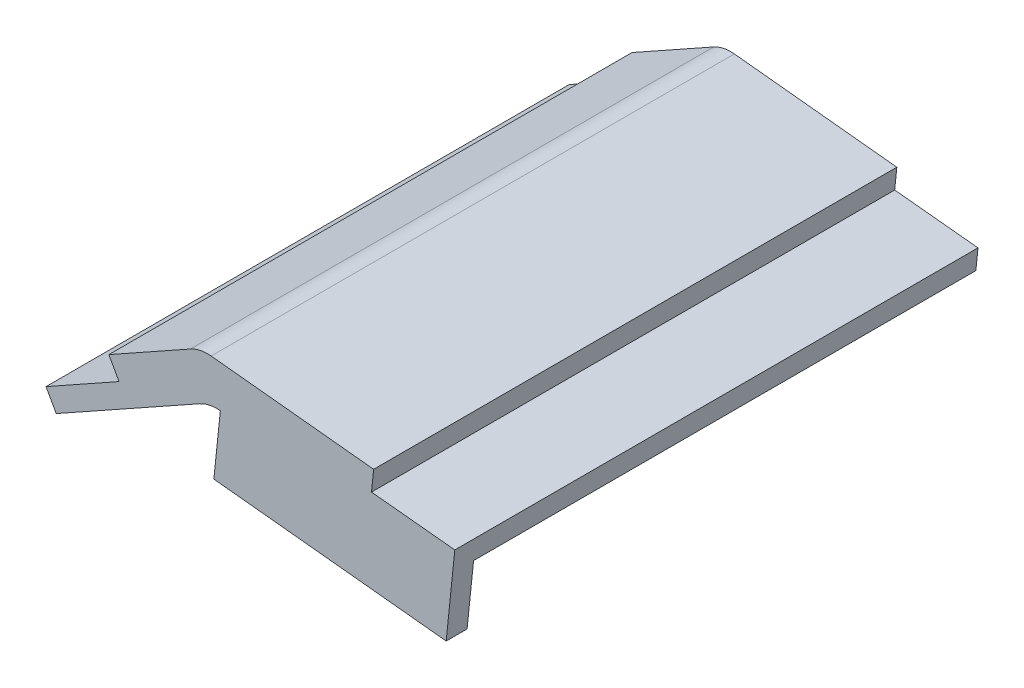
SolidWorks part; units mm, degrees
ref_plane "Front Plane" through (0, 0, 0) normal (0, 0, 1) x (1, 0, 0)
ref_plane "Top Plane" through (0, 0, 0) normal (0, 1, 0) x (1, 0, 0)
ref_plane "Right Plane" through (0, 0, 0) normal (1, 0, 0) x (0, 0, -1)
sketch "Sketch1" plane through (0, 0, 0) normal (0, 0, 1) x (1, 0, 0)
  line L0 (11.576, 13.6218) -> (13.0406, 11.0036)
  line L1 (11.576, 13.6218) -> (23.2849, 20.1718)
  line L2 (26.242, 20.7814) -> (49.5333, 18.3641)
  line L3 (49.5333, 18.3641) -> (49.2314, 15.3793)
  line L4 (24.6669, 20.9449) -> (28.6211, 2.527) construction
  line L5 (13.0406, 11.0036) -> (2.5678, 5.1452)
  line L6 (2.5678, 5.1452) -> (4.0325, 2.527)
  line L7 (4.0325, 2.527) -> (24.6026, 14.0339)
  line L8 (27.5598, 14.6436) -> (60.8607, 11.1874)
  line L9 (49.2314, 15.3793) -> (61.1704, 14.1714)
  line L10 (61.1704, 14.1714) -> (60.8607, 11.1874)
  line L11 (28.6211, 2.527) -> (50028.6211, 2.527) construction
  arc A0 (26.242, 20.7814) -> (23.2849, 20.1718) centre (25.7259, 15.8081) ccw
  arc A1 (27.5598, 14.6436) -> (24.6026, 14.0339) centre (27.0436, 9.6703) ccw
  dimension "D9" = 5
  dimension "D10" = 5
  dimension "D1" = 25
  dimension "D2" = 15
  dimension "D3" = 12
  dimension "D4" = 12
  dimension "D5" = 3
  dimension "D6" = 3
  dimension "D7" = 3
  dimension "D8" = 3
  dimension "D11" = 145
extrude "Boss-Extrude1" add sketch "Sketch1" along normal blind 75
sketch "Sketch2" plane through (1.7973, 17.3174, 0) normal (-0.1032, -0.9947, 0) x (0.9947, -0.1032, 0)
  line L0 (59.3807, 75) -> (59.3807, 0) construction
  line L1 (25.9009, 75) -> (59.3807, 75)
  line L2 (25.9009, 75) -> (25.9009, 72)
  line L3 (25.9009, 72) -> (59.3807, 72)
  line L4 (59.3807, 75) -> (59.3807, 72)
  dimension "D1" = 3
extrude "Boss-Extrude2" add sketch "Sketch2" along normal blind 9
